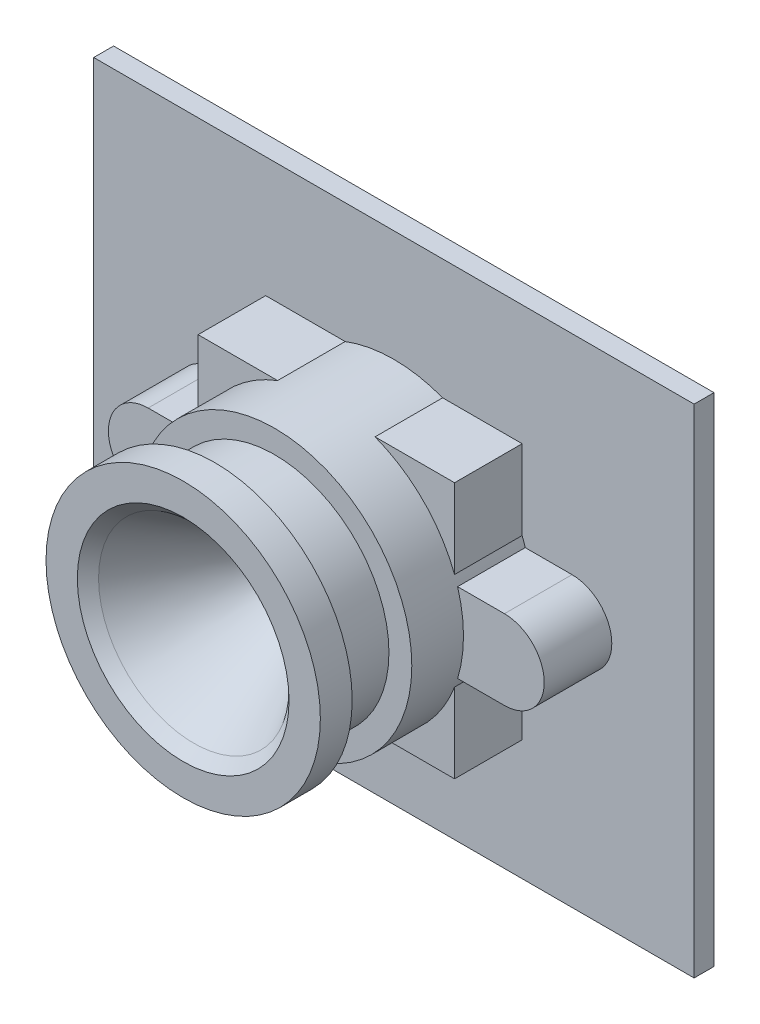
SolidWorks part; units mm, degrees
ref_plane "Front Plane" through (0, 0, 0) normal (0, 0, 1) x (1, 0, 0)
ref_plane "Top Plane" through (0, 0, 0) normal (0, 1, 0) x (1, 0, 0)
ref_plane "Right Plane" through (0, 0, 0) normal (1, 0, 0) x (0, 0, -1)
sketch "Sketch1" plane through (0, 0, 0) normal (0, 0, 1) x (1, 0, 0)
  line L1 (15.1, -12.5) -> (-15.1, -12.5)
  line L2 (15.1, -12.5) -> (15.1, 12.5)
  line L3 (15.1, 12.5) -> (-15.1, 12.5)
  line L4 (-15.1, -12.5) -> (-15.1, 12.5)
  line L5 (15.1, -12.5) -> (-15.1, 12.5) construction
  line L6 (15.1, 12.5) -> (-15.1, -12.5) construction
  point P0 (0, 0)
  dimension "D1" = 30.2
  dimension "D2" = 25
extrude "Boss-Extrude1" add sketch "Sketch1" along normal blind 1
sketch "Sketch2" plane through (0, 0, 1) normal (0, 0, 1) x (1, 0, 0)
  line L1 (6.45, -6.45) -> (-6.45, -6.45)
  line L2 (6.45, -6.45) -> (6.45, 6.45)
  line L3 (6.45, 6.45) -> (-6.45, 6.45)
  line L4 (-6.45, -6.45) -> (-6.45, 6.45)
  line L5 (6.45, -6.45) -> (-6.45, 6.45) construction
  line L6 (6.45, 6.45) -> (-6.45, -6.45) construction
  point P0 (0, 0)
  dimension "D1" = 12.9
extrude "Boss-Extrude2" add sketch "Sketch2" along normal blind 3.4
sketch "Sketch3" plane through (0, 0, 1) normal (0, 0, 1) x (1, 0, 0)
  circle A0 centre (0, 0) radius 6.9
  dimension "D1" = 13.8
extrude "Boss-Extrude3" add sketch "Sketch3" along normal blind 6
sketch "Sketch4" plane through (0, 0, 7) normal (0, 0, 1) x (1, 0, 0)
  circle A0 centre (0, 0) radius 5.75
  dimension "D1" = 11.5
extrude "Boss-Extrude4" add sketch "Sketch4" along normal blind 3
sketch "Sketch5" plane through (0, 0, 10) normal (0, 0, 1) x (1, 0, 0)
  circle A1 centre (0, 0) radius 6.9
  circle A2 centre (0, 0) radius 6.9 construction
extrude "Boss-Extrude5" add sketch "Sketch5" along normal blind 1.6
sketch "Sketch6" plane through (0, 0, 11.6) normal (0, 0, 1) x (1, 0, 0)
  circle A0 centre (0, 0) radius 5.125
  dimension "D1" = 10.25
extrude "Cut-Extrude1" cut sketch "Sketch6" against normal blind 5.65 draft 32
chamfer "Chamfer1" distance 0.2 angle 45 1 edges at (5.125, 0, 11.6)
sketch "Sketch7" plane through (0, 0, 0) normal (0, 0, -1) x (-1, 0, 0)
  line L0 (15.1, -12.5) -> (-15.1, -12.5) construction
  line L1 (1.8, -12.5) -> (9.1, -12.5)
  line L2 (1.8, -12.5) -> (1.8, -8.1)
  line L3 (1.8, -8.1) -> (9.1, -8.1)
  line L4 (9.1, -12.5) -> (9.1, -8.1)
  line L5 (15.1, 12.5) -> (15.1, -12.5) construction
  dimension "D1" = 7.3
  dimension "D2" = 4.4
  dimension "D3" = 6
extrude "Boss-Extrude6" add sketch "Sketch7" along normal blind 3.25 separate body
sketch "Sketch8" plane through (0, -12.5, 0) normal (0, -1, 0) x (1, 0, 0)
  line L1 (-8.7, -0.4) -> (-2.2, -0.4)
  line L2 (-9.1, 0) -> (-1.8, 0) construction
  line L3 (-9.1, 0) -> (-9.1, -3.25) construction
  line L4 (-9.1, -3.25) -> (-1.8, -3.25) construction
  line L5 (-1.8, 0) -> (-1.8, -3.25) construction
  line L6 (-2.2, -0.4) -> (-2.2, -2.85)
  line L7 (-8.7, -2.85) -> (-2.2, -2.85)
  line L8 (-8.7, -0.4) -> (-8.7, -2.85)
  dimension "D1" = 0.4
extrude "Cut-Extrude2" cut sketch "Sketch8" against normal blind 4
sketch "Sketch9" plane through (0, 0, 4.4) normal (0, 0, 1) x (1, 0, 0)
  line L0 (8.96, 0) -> (-8.96, 0) construction
  line L1 (8.96, -2) -> (-8.96, -2)
  line L2 (8.96, 2) -> (-8.96, 2)
  arc A0 (8.96, -2) -> (8.96, 2) centre (8.96, 0) ccw
  arc A1 (-8.96, 2) -> (-8.96, -2) centre (-8.96, 0) ccw
  point P2 (0, 0)
  point P8 (-10.96, 0)
  point P9 (10.96, 0)
  dimension "D1" = 4
  dimension "D2" = 21.92
extrude "Boss-Extrude7" add sketch "Sketch9" against normal up to surface (3.4 mm away) up to face at (0, 0, 1)
